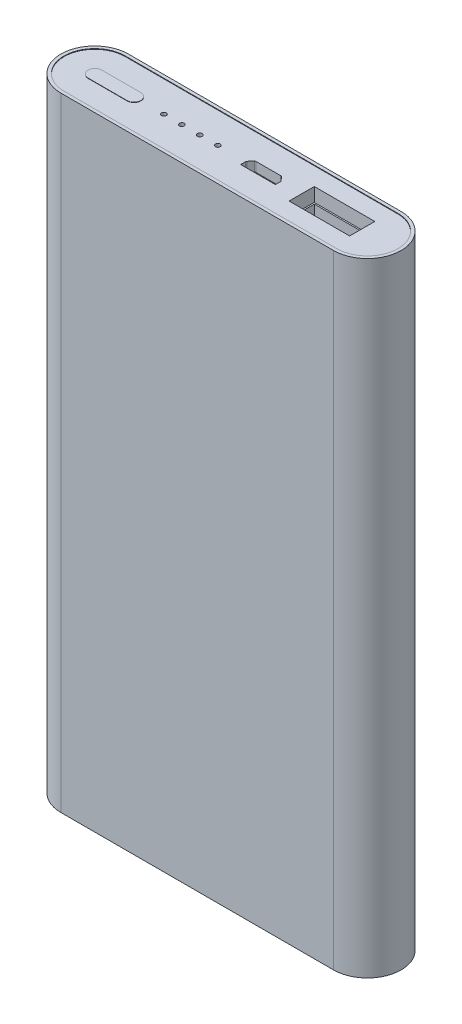
SolidWorks part; units mm, degrees
ref_plane "Front Plane" through (0, 0, 0) normal (0, 0, 1) x (1, 0, 0)
ref_plane "Top Plane" through (0, 0, 0) normal (0, 1, 0) x (1, 0, 0)
ref_plane "Right Plane" through (0, 0, 0) normal (1, 0, 0) x (0, 0, -1)
sketch "Sketch1" plane through (0, 0, 0) normal (0, 1, 0) x (1, 0, 0)
  line L0 (-28.45, 0) -> (28.45, 0) construction
  line L1 (-28.45, 7.05) -> (28.45, 7.05)
  line L2 (-28.45, -7.05) -> (28.45, -7.05)
  line L3 (-28.45, 6.38) -> (28.45, 6.38)
  line L4 (-28.45, -6.38) -> (28.45, -6.38)
  arc A0 (-28.45, 7.05) -> (-28.45, -7.05) centre (-28.45, 0) ccw
  arc A1 (28.45, -7.05) -> (28.45, 7.05) centre (28.45, 0) ccw
  arc A2 (28.45, -6.38) -> (28.45, 6.38) centre (28.45, 0) ccw
  arc A3 (-28.45, 6.38) -> (-28.45, -6.38) centre (-28.45, 0) ccw
  point P3 (0, 0)
  dimension "D2" = 56.9
  dimension "D1" = 14.1
  dimension "D3" = 0.67
extrude "Boss-Extrude1" add sketch "Sketch1" along normal mid plane 130
ref_plane "Plane1" through (0, 64.875, 0) normal (0, 1, 0) x (1, 0, 0)
sketch "Sketch2" plane through (0, 64.875, 0) normal (0, 1, 0) x (1, 0, 0)
  line L0 (-28.45, -6.38) -> (28.45, -6.38) construction
  line L1 (28.45, 6.38) -> (-28.45, 6.38) construction
  line L2 (-28.45, -6.38) -> (28.45, -6.38)
  line L3 (28.45, 6.38) -> (-28.45, 6.38)
  arc A0 (28.45, -6.38) -> (28.45, 6.38) centre (28.45, 0) ccw construction
  arc A1 (-28.45, 6.38) -> (-28.45, -6.38) centre (-28.45, 0) ccw construction
  arc A2 (28.45, -6.38) -> (28.45, 6.38) centre (28.45, 0) ccw
  arc A3 (-28.45, 6.38) -> (-28.45, -6.38) centre (-28.45, 0) ccw
extrude "Boss-Extrude2" add sketch "Sketch2" against normal blind 129.75
sketch "Sketch3" plane through (0, 0, -7.05) normal (0, 0, -1) x (-1, 0, 0)
  line L0 (-28.45, -65) -> (28.45, -65) construction
  line L1 (-4.125, -33) -> (4.125, -33)
  line L2 (-4.125, -33) -> (-4.125, -38.5)
  line L3 (-4.125, -38.5) -> (4.125, -38.5)
  line L4 (4.125, -33) -> (4.125, -38.5)
  line L5 (-4.125, -33) -> (4.125, -38.5) construction
  line L6 (-4.125, -38.5) -> (4.125, -33) construction
  point P0 (0, -35.75)
  dimension "D1" = 5.5
  dimension "D2" = 8.25
  dimension "D3" = 32
sketch "Sketch4" plane through (0, 0, -7.05) normal (0, 0, -1) x (-1, 0, 0)
  line L0 (45.8047, 111.7512) -> (245.8047, 111.7512) construction
sketch "Sketch5" plane through (0, 0, -7.05) normal (0, 0, -1) x (-1, 0, 0)
  line L0 (159.3417, 271.5) -> (812.675, 271.5) construction
  line L1 (-4.125, -38.5) -> (4.125, -38.5) construction
  line L2 (-4.125, -33) -> (4.125, -33) construction
  line L3 (3.048, -38.5) -> (4.3698, -38.5)
  line L4 (4.3698, -38.5) -> (4.3698, -33)
  line L5 (4.3698, -33) -> (3.0393, -33)
  line L6 (-4.125, -33) -> (-4.125, -38.5)
  line L7 (-4.125, -38.5) -> (-2.775, -38.5)
  line L8 (-2.775, -38.5) -> (-2.775, -34.15)
  line L9 (-2.775, -34.15) -> (-0.025, -34.15)
  line L10 (3.0393, -33) -> (3.048, -38.5)
  line L11 (-1.755, -38.5) -> (-1.755, -35.122)
  line L12 (1.975, -38.5) -> (1.975, -34.3306)
  line L13 (0.4571, -33) -> (-4.125, -33)
  line L14 (-1.755, -35.122) -> (-0.365, -35.122)
  line L15 (-0.365, -35.122) -> (-0.365, -38.5)
  line L16 (-0.365, -38.5) -> (-1.755, -38.5)
  line L17 (1.975, -38.5) -> (0.675, -38.5)
  line L18 (0.675, -38.5) -> (0.675, -35)
  arc A0 (0.675, -35) -> (-0.025, -34.15) centre (-0.1749, -34.9867) ccw
  spline S1 degree 3 poles (1.975, -34.3306) (1.9466, -34.3016) (1.957, -34.2482) (1.949, -34.2153) (1.9243, -34.1142) (1.9165, -34.0425) (1.8709, -33.9492) (1.8437, -33.8936) (1.8201, -33.8363) (1.7929, -33.7806) (1.7586, -33.7106) (1.6991, -33.6338) (1.6454, -33.5766) (1.2802, -33.1875) (1.0168, -33.0477) (0.4571, -33) knots 0 0 0 0 1 1 1 2 2 2 3 3 3 4 4 4 5 5 5 5
  dimension "D5" = 0.85
  dimension "D1" = 1.35
  dimension "D2" = 4.35
  dimension "D3" = 2.75
  dimension "D4" = 3.5
  dimension "D6" = 2.37
  dimension "D7" = 1.39
  dimension "D8" = 3.378
  dimension "D9" = 4.8
  dimension "D10" = 1.3
extrude "Cut-Extrude1" cut sketch "Sketch5" against normal blind 0.25
sketch "Sketch8" plane through (0, 64.875, 0) normal (0, 1, 0) x (1, 0, 0)
  circle A0 centre (-14, 0) radius 0.5
  arc A1 (-28.45, 7.05) -> (-28.45, -7.05) centre (-28.45, 0) ccw construction
  circle A2 centre (-10.25, 0) radius 0.5
  circle A3 centre (-6.5, 0) radius 0.5
  circle A4 centre (-2.75, 0) radius 0.5
  point P5 (-35.5, 0)
  dimension "D1" = 1
  dimension "D2" = 21.5
  dimension "D4" = 3.75
  dimension "D3" = 4
extrude "Cut-Extrude2" cut sketch "Sketch8" against normal blind 2
sketch "Sketch9" plane through (0, 64.875, 0) normal (0, 1, 0) x (1, 0, 0)
  line L0 (-28.375, 0) -> (-20.25, 0) construction
  line L1 (-28.375, 1.4375) -> (-20.25, 1.4375)
  line L2 (-28.375, -1.4375) -> (-20.25, -1.4375)
  arc A0 (-28.375, 1.4375) -> (-28.375, -1.4375) centre (-28.375, 0) ccw
  arc A1 (-20.25, -1.4375) -> (-20.25, 1.4375) centre (-20.25, 0) ccw
  circle A2 centre (-14, 0) radius 0.5 construction
  circle A3 centre (-14, 0) radius 0.5 construction
  point P3 (-24.3125, 0)
  point P8 (-29.8125, 0)
  point P9 (-18.8125, 0)
  dimension "D1" = 2.875
  dimension "D2" = 11
  dimension "D3" = 6.25
extrude "Boss-Extrude3" add sketch "Sketch9" along normal blind 0.0625
sketch "Sketch10" plane through (0, 64.875, 0) normal (0, 1, 0) x (1, 0, 0)
  line L0 (-28.375, -1.5625) -> (-20.25, -1.5625)
  line L1 (-20.25, 1.5625) -> (-28.375, 1.5625)
  line L4 (-20.25, 1.4375) -> (-28.375, 1.4375)
  line L5 (-28.375, -1.4375) -> (-20.25, -1.4375)
  line L8 (-20.25, 1.4375) -> (-28.375, 1.4375)
  line L9 (-20.25, 1.4375) -> (-28.375, 1.4375)
  line L10 (-28.375, -1.4375) -> (-20.25, -1.4375)
  line L11 (-28.375, -1.4375) -> (-20.25, -1.4375)
  arc A0 (-28.375, 1.5625) -> (-28.375, -1.5625) centre (-28.375, 0) ccw
  arc A1 (-20.25, -1.4375) -> (-20.25, 1.4375) centre (-20.25, 0) ccw
  arc A2 (-20.25, -1.4375) -> (-20.25, 1.4375) centre (-20.25, 0) ccw
  arc A3 (-20.25, -1.5625) -> (-20.25, 1.5625) centre (-20.25, 0) ccw
  circle A4 centre (-14, 0) radius 0.5 construction
  circle A5 centre (-14, 0) radius 0.5 construction
  arc A6 (-20.25, -1.4375) -> (-20.25, 1.4375) centre (-20.25, 0) ccw
  arc A7 (-28.375, 1.4375) -> (-28.375, -1.4375) centre (-28.375, 0) ccw
  arc A10 (-28.375, 1.4375) -> (-28.375, -1.4375) centre (-28.375, 0) ccw
  arc A11 (-28.375, 1.4375) -> (-28.375, -1.4375) centre (-28.375, 0) ccw
  dimension "D1" = 0
  dimension "D3" = 0.125
sketch "Sketch11" plane through (0, 64.875, 0) normal (0, 1, 0) x (1, 0, 0)
  line L1 (14.75, 2.625) -> (27.375, 2.625)
  line L2 (14.75, 2.625) -> (14.75, -2.625)
  line L3 (14.75, -2.625) -> (27.375, -2.625)
  line L4 (27.375, 2.625) -> (27.375, -2.625)
  line L5 (14.75, 2.625) -> (27.375, -2.625) construction
  line L6 (14.75, -2.625) -> (27.375, 2.625) construction
  arc A0 (28.45, -7.05) -> (28.45, 7.05) centre (28.45, 0) ccw construction
  point P0 (21.0625, 0)
  point P5 (21.0625, 2.625)
  point P11 (35.5, 0)
  dimension "D1" = 5.25
  dimension "D2" = 12.625
  dimension "D3" = 20.75
extrude "Cut-Extrude4" cut sketch "Sketch11" against normal blind 11.75
sketch "Sketch12" plane through (0, 53.125, 0) normal (0, 1, 0) x (1, 0, 0)
  line L0 (27.375, -2.625) -> (27.375, 2.625) construction
  line L1 (14.75, -2.625) -> (27.375, -2.625) construction
  line L2 (27.375, 2.625) -> (14.75, 2.625) construction
  line L3 (14.75, 2.625) -> (14.75, -2.625) construction
  line L4 (27.375, -2.625) -> (27.375, 2.625)
  line L5 (14.75, -2.625) -> (27.375, -2.625)
  line L6 (27.375, 2.625) -> (14.75, 2.625)
  line L7 (14.75, 2.625) -> (14.75, -2.625)
  line L8 (15.05, 2.325) -> (15.05, -2.325)
  line L9 (15.05, -2.325) -> (27.075, -2.325)
  line L10 (27.075, -2.325) -> (27.075, 2.325)
  line L11 (27.075, 2.325) -> (15.05, 2.325)
  dimension "D1" = 0.3
extrude "Boss-Extrude4" add sketch "Sketch12" along normal blind 8.875
sketch "Sketch13" plane through (0, 53.125, 0) normal (0, 1, 0) x (1, 0, 0)
  line L0 (15.05, 2.325) -> (15.05, -2.325) construction
  line L1 (15.3, -0.39) -> (26.825, -0.39)
  line L2 (15.3, -0.39) -> (15.3, -1.95)
  line L3 (15.3, -1.95) -> (26.825, -1.95)
  line L4 (26.825, -0.39) -> (26.825, -1.95)
  line L5 (27.075, -2.325) -> (27.075, 2.325) construction
  line L6 (15.05, -2.325) -> (27.075, -2.325) construction
  dimension "D1" = 0.25
  dimension "D2" = 0.25
  dimension "D3" = 0.375
  dimension "D4" = 1.56
extrude "Boss-Extrude5" add sketch "Sketch13" along normal up to surface (8.875 mm away) up to face at (21.0625, 62, 0)
sketch "Sketch15" plane through (0, -64.875, 0) normal (0, -1, 0) x (1, 0, 0)
  line L0 (-224.2606, -53.3177) -> (-2328.9272, -53.3177) construction
sketch "Sketch16" plane through (0, 64.875, 0) normal (0, 1, 0) x (1, 0, 0)
  line L0 (4.1111, 1.08) -> (9.3389, 1.08)
  line L1 (3.1742, 0.1648) -> (3.8854, 0.9776)
  line L2 (3.1, -0.0327) -> (3.1, -1.08)
  line L3 (3.1, -1.08) -> (10.35, -1.08)
  line L4 (10.35, -0.0327) -> (10.35, -1.08)
  line L5 (9.5646, 0.9776) -> (10.2758, 0.1648)
  line L6 (14.75, 2.625) -> (14.75, -2.625) construction
  line L7 (6.725, 1.08) -> (6.725, -1.08) construction
  line L8 (6.725, 0) -> (4.8888, 0) construction
  arc A0 (10.35, -0.0327) -> (10.2758, 0.1648) centre (10.05, -0.0327) ccw
  arc A1 (9.5646, 0.9776) -> (9.3389, 1.08) centre (9.3389, 0.78) ccw
  arc A2 (4.1111, 1.08) -> (3.8854, 0.9776) centre (4.1111, 0.78) ccw
  arc A3 (3.1, -0.0327) -> (3.1742, 0.1648) centre (3.4, -0.0327) cw
  point P6 (6.725, -1.08)
  point P7 (6.725, 1.08)
  point P20 (9.475, 1.08)
  point P23 (3.975, 1.08)
  point P26 (3.1, 0.08)
  dimension "D6" = 0.3
  dimension "D1" = 7.25
  dimension "D2" = 1.16
  dimension "D3" = 2.16
  dimension "D4" = 5.5
  dimension "D5" = 4.4
extrude "Cut-Extrude5" cut sketch "Sketch16" against normal blind 10
sketch "Sketch17" plane through (0, 54.875, 0) normal (0, 1, 0) x (1, 0, 0)
  line L0 (3.1, -1.08) -> (10.35, -1.08) construction
  line L1 (3.975, -0.83) -> (9.475, -0.83)
  line L2 (3.975, -0.83) -> (3.975, -0.705)
  line L3 (3.975, -0.705) -> (9.475, -0.705)
  line L4 (9.475, -0.83) -> (9.475, -0.705)
  line L5 (6.725, -1.08) -> (6.725, 0.6846) construction
  line L6 (3.1, -1.08) -> (10.35, -1.08) construction
  dimension "D1" = 0.375
  dimension "D2" = 5.5
  dimension "D3" = 0.125
extrude "Boss-Extrude6" add sketch "Sketch17" along normal blind 8.1
sketch "Sketch18" plane through (0, 54.875, 0) normal (0, 1, 0) x (1, 0, 0)
  line L0 (3.1, -1.08) -> (10.35, -1.08) construction
  line L1 (10.35, -1.08) -> (10.35, -0.0327) construction
  line L2 (10.2758, 0.1648) -> (9.5646, 0.9776) construction
  line L3 (9.3389, 1.08) -> (4.1111, 1.08) construction
  line L4 (3.8854, 0.9776) -> (3.1742, 0.1648) construction
  line L5 (3.1, -1.08) -> (10.35, -1.08)
  line L6 (10.35, -1.08) -> (10.35, -0.0327)
  line L7 (10.2758, 0.1648) -> (9.5646, 0.9776)
  line L8 (9.3389, 1.08) -> (4.1111, 1.08)
  line L9 (3.8854, 0.9776) -> (3.1742, 0.1648)
  line L10 (3.1, -0.0327) -> (3.1, -1.08) construction
  line L11 (3.1, -0.0327) -> (3.1, -1.08)
  line L12 (3.225, -0.0327) -> (3.225, -0.955)
  line L13 (3.225, -0.955) -> (10.225, -0.955)
  line L14 (10.225, -0.955) -> (10.225, -0.0327)
  line L15 (10.1817, 0.0825) -> (9.4706, 0.8952)
  line L16 (9.3389, 0.955) -> (4.1111, 0.955)
  line L17 (3.9794, 0.8952) -> (3.2683, 0.0825)
  arc A0 (3.1742, 0.1648) -> (3.1, -0.0327) centre (3.4, -0.0327) ccw construction
  arc A1 (10.35, -0.0327) -> (10.2758, 0.1648) centre (10.05, -0.0327) ccw construction
  arc A2 (9.5646, 0.9776) -> (9.3389, 1.08) centre (9.3389, 0.78) ccw construction
  arc A3 (3.1742, 0.1648) -> (3.1, -0.0327) centre (3.4, -0.0327) ccw construction
  arc A4 (4.1111, 1.08) -> (3.8854, 0.9776) centre (4.1111, 0.78) ccw construction
  arc A5 (3.1742, 0.1648) -> (3.1, -0.0327) centre (3.4, -0.0327) ccw
  arc A6 (10.35, -0.0327) -> (10.2758, 0.1648) centre (10.05, -0.0327) ccw
  arc A7 (9.5646, 0.9776) -> (9.3389, 1.08) centre (9.3389, 0.78) ccw
  arc A8 (3.1742, 0.1648) -> (3.1, -0.0327) centre (3.4, -0.0327) ccw
  arc A9 (4.1111, 1.08) -> (3.8854, 0.9776) centre (4.1111, 0.78) ccw
  arc A10 (10.225, -0.0327) -> (10.1817, 0.0825) centre (10.05, -0.0327) ccw
  arc A11 (9.4706, 0.8952) -> (9.3389, 0.955) centre (9.3389, 0.78) ccw
  arc A12 (4.1111, 0.955) -> (3.9794, 0.8952) centre (4.1111, 0.78) ccw
  arc A13 (3.2683, 0.0825) -> (3.225, -0.0327) centre (3.4, -0.0327) ccw
  arc A14 (3.2683, 0.0825) -> (3.225, -0.0327) centre (3.4, -0.0327) ccw
  line M2 (10.35, -1.08) -> (10.35, -0.0327)
  arc M3 (10.35, -0.0327) -> (10.2758, 0.1648) centre (10.05, -0.0327) ccw
  line M4 (10.2758, 0.1648) -> (9.5646, 0.9776)
  arc M5 (9.5646, 0.9776) -> (9.3389, 1.08) centre (9.3389, 0.78) ccw
  line M6 (9.3389, 1.08) -> (4.1111, 1.08)
  arc M7 (4.1111, 1.08) -> (3.8854, 0.9776) centre (4.1111, 0.78) ccw
  line M8 (3.8854, 0.9776) -> (3.1742, 0.1648)
  arc M9 (3.1742, 0.1648) -> (3.1, -0.0327) centre (3.4, -0.0327) ccw
  line M10 (3.1, -0.0327) -> (3.1, -1.08)
  line M11 (3.1, -1.08) -> (10.35, -1.08)
  line M15 (9.475, -0.83) -> (3.975, -0.83)
  dimension "D1" = 0.125
extrude "Boss-Extrude7" add sketch "Sketch18" along normal blind 8 contours A13 L17 A12 L16 A11 L15 A10 L14 L13 L12 M11 M2 M3 M4 M5 M6 M7 M8 M9 M10 M15
sketch "Sketch19" plane through (0, 0, 7.05) normal (0, 0, 1) x (1, 0, 0)
  line L0 (212.3437, 772.9713) -> (1178.3437, 772.9713) construction
  line L1 (-7.3786, -55) -> (8.5451, -55) construction
  line L2 (-28.45, -65) -> (28.45, -65) construction
  dimension "D1" = 10
